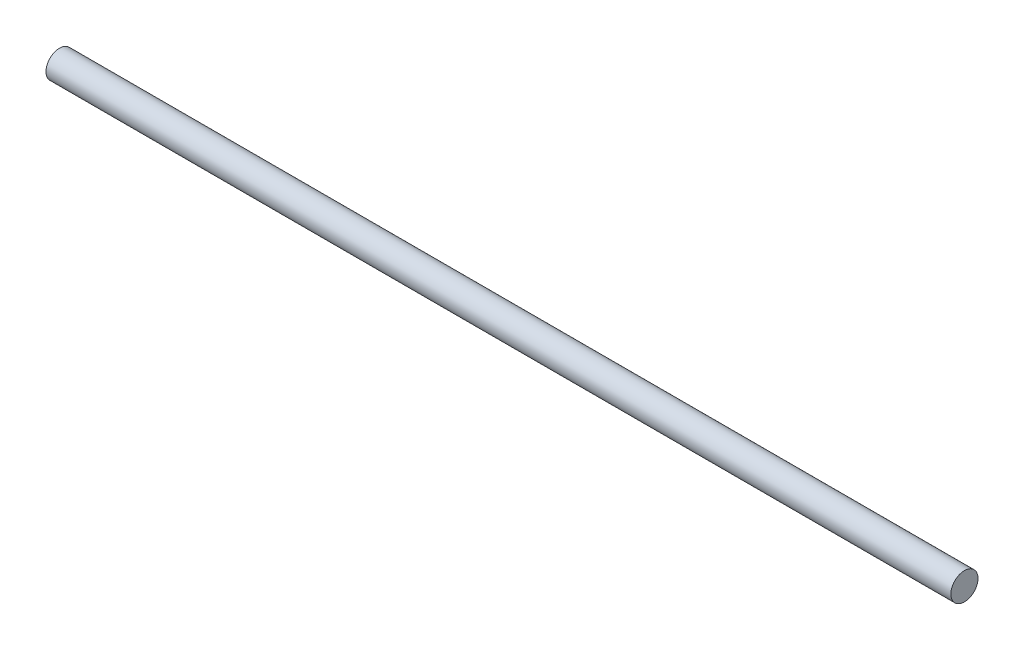
SolidWorks part; units mm, degrees
ref_plane "Plan de face" through (0, 0, 0) normal (0, 0, 1) x (1, 0, 0)
ref_plane "Plan de dessus" through (0, 0, 0) normal (0, 1, 0) x (1, 0, 0)
ref_plane "Plan de droite" through (0, 0, 0) normal (1, 0, 0) x (0, 0, -1)
sketch "Esquisse1" plane through (0, 0, 0) normal (1, 0, 0) x (0, 0, -1)
  circle A0 centre (0, 0) radius 15
  dimension "D1" = 30
extrude "Boss.-Extru.1" add sketch "Esquisse1" along normal blind 1000
